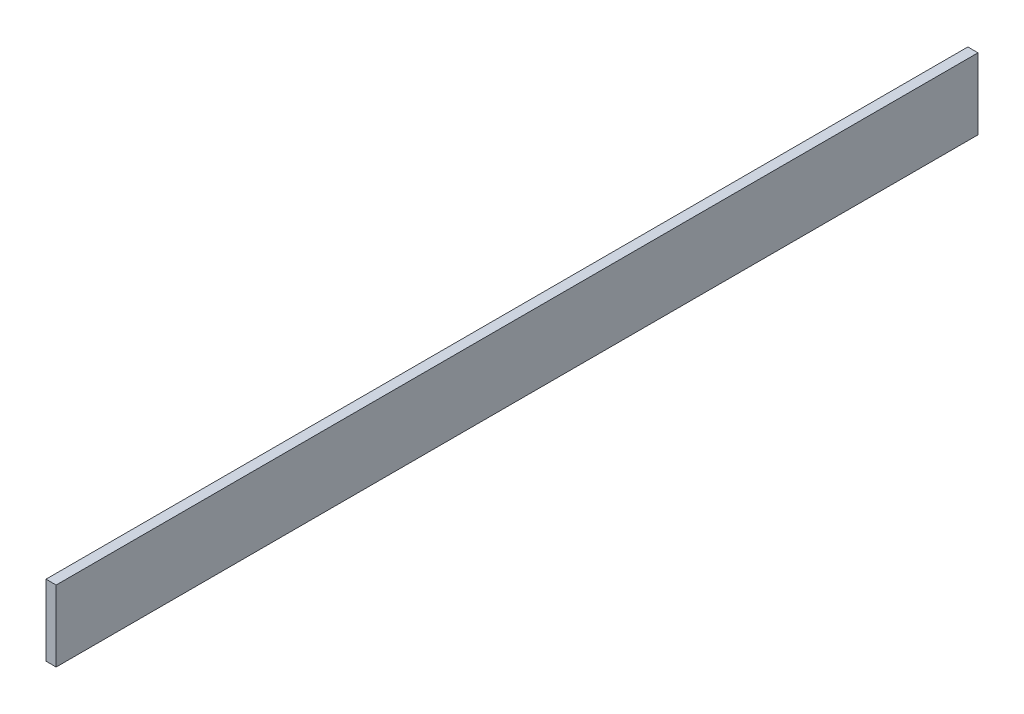
SolidWorks part; units mm, degrees
ref_plane "Front Plane" through (0, 0, 0) normal (0, 0, 1) x (1, 0, 0)
ref_plane "Top Plane" through (0, 0, 0) normal (0, 1, 0) x (1, 0, 0)
ref_plane "Right Plane" through (0, 0, 0) normal (1, 0, 0) x (0, 0, -1)
sketch "Sketch1" plane through (0, 0, 0) normal (0, 0, 1) x (1, 0, 0)
  line L1 (0, 0) -> (3.175, 0)
  line L2 (0, 0) -> (0, 22.225)
  line L3 (0, 22.225) -> (3.175, 22.225)
  line L4 (3.175, 0) -> (3.175, 22.225)
  dimension "D1" = 3.175
  dimension "D2" = 22.225
extrude "Boss-Extrude1" add sketch "Sketch1" along normal blind 288.29
